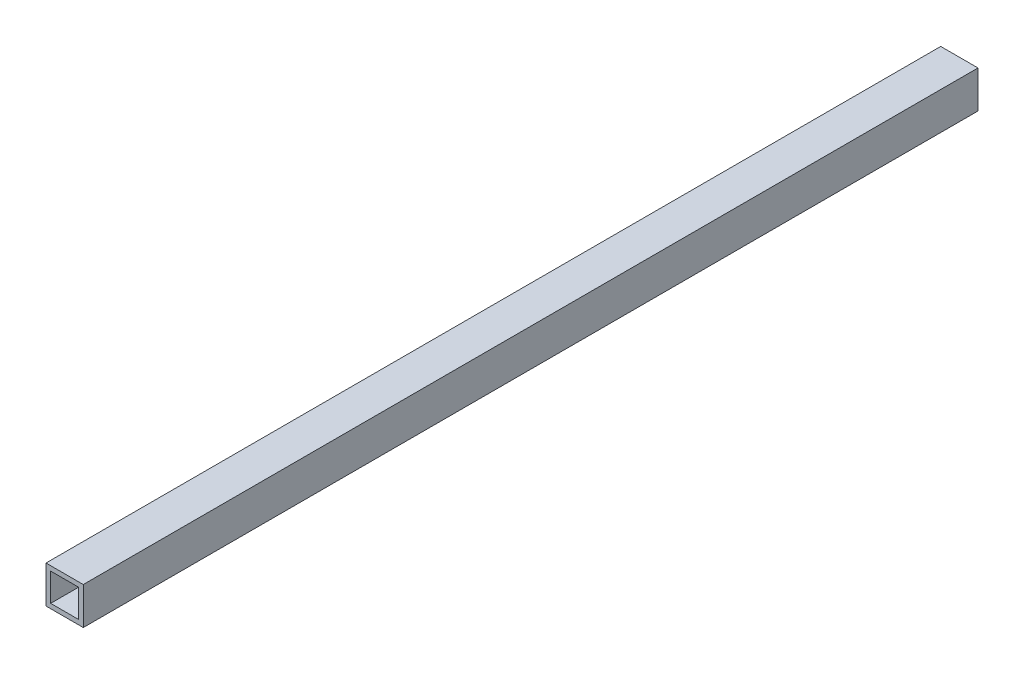
SolidWorks part; units mm, degrees
ref_plane "Front Plane" through (0, 0, 0) normal (0, 0, 1) x (1, 0, 0)
ref_plane "Top Plane" through (0, 0, 0) normal (0, 1, 0) x (1, 0, 0)
ref_plane "Right Plane" through (0, 0, 0) normal (1, 0, 0) x (0, 0, -1)
sketch "Sketch1" plane through (0, 0, 0) normal (0, 0, 1) x (1, 0, 0)
  line L5 (12.7, 12.7) -> (-12.7, 12.7)
  line L6 (12.7, 12.7) -> (12.7, -12.7)
  line L7 (12.7, -12.7) -> (-12.7, -12.7)
  line L8 (-12.7, 12.7) -> (-12.7, -12.7)
  line L9 (12.7, 12.7) -> (-12.7, -12.7) construction
  line L10 (12.7, -12.7) -> (-12.7, 12.7) construction
  line L15 (9.525, 9.525) -> (-9.525, 9.525)
  line L16 (9.525, 9.525) -> (9.525, -9.525)
  line L17 (9.525, -9.525) -> (-9.525, -9.525)
  line L18 (-9.525, 9.525) -> (-9.525, -9.525)
  line L19 (9.525, 9.525) -> (-9.525, -9.525) construction
  line L20 (9.525, -9.525) -> (-9.525, 9.525) construction
  point P0 (0, 0)
  point P6 (0, 0)
  dimension "D1" = 3.175
  dimension "D2" = 25.4
  dimension "D3" = 25.4
extrude "Boss-Extrude1" add sketch "Sketch1" along normal blind 609.6
